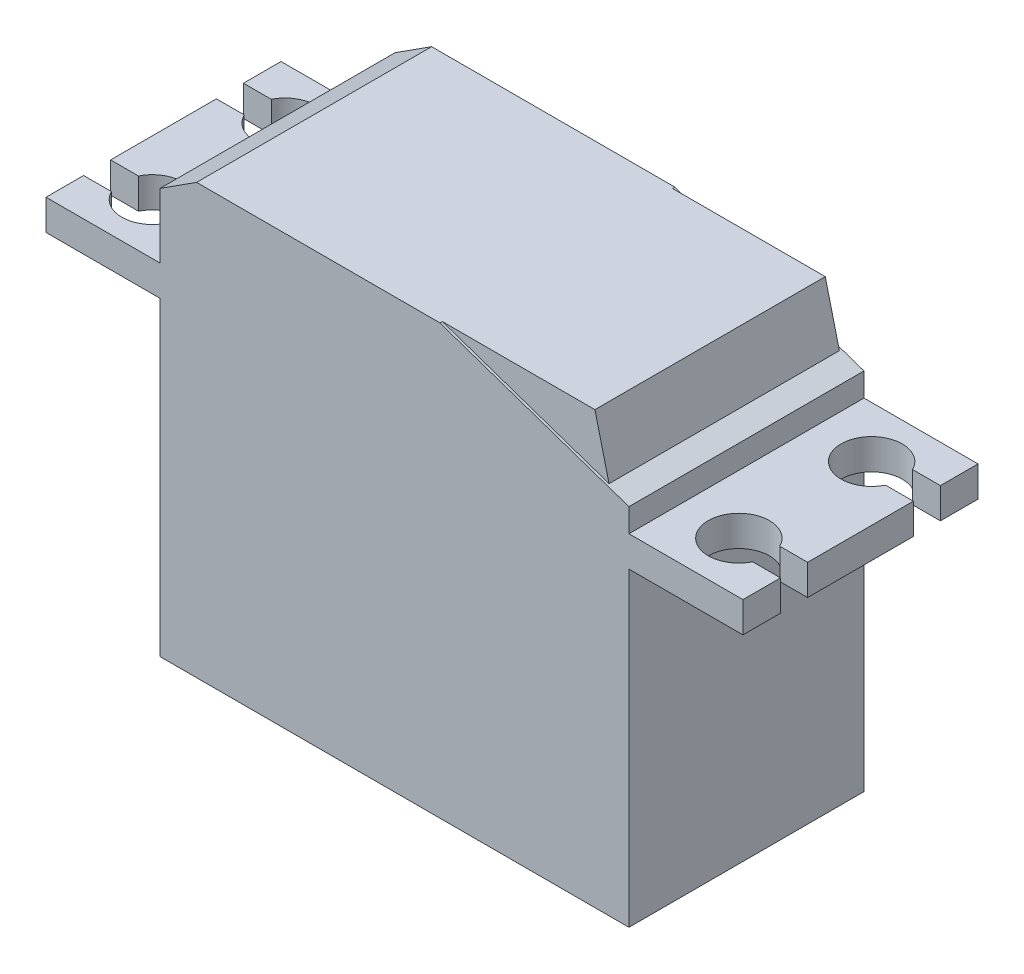
SolidWorks part; units mm, degrees
ref_plane "정면" through (0, 0, 0) normal (0, 0, 1) x (1, 0, 0)
ref_plane "윗면" through (0, 0, 0) normal (0, 1, 0) x (1, 0, 0)
ref_plane "우측면" through (0, 0, 0) normal (1, 0, 0) x (0, 0, -1)
sketch "Sketch1" plane through (0, 0, 0) normal (0, 1, 0) x (1, 0, 0)
  line L1 (-19.95, 10) -> (19.95, 10)
  line L2 (-19.95, 10) -> (-19.95, -10)
  line L3 (-19.95, -10) -> (19.95, -10)
  line L4 (19.95, 10) -> (19.95, -10)
  line L5 (-19.95, 10) -> (19.95, -10) construction
  line L6 (-19.95, -10) -> (19.95, 10) construction
  point P0 (0, 0)
  dimension "D1" = 20
  dimension "D2" = 39.9
extrude "Boss-Extrude1" add sketch "Sketch1" along normal mid plane 36.5
sketch "Sketch2" plane through (19.95, 0, 0) normal (1, 0, 0) x (0, 0, -1)
  line L0 (-10, 8.15) -> (10, 8.15)
  line L1 (-10, 18.25) -> (-10, -18.25) construction
  line L2 (10, 18.25) -> (10, -18.25) construction
  line L3 (-10, -18.25) -> (10, -18.25) construction
  line L4 (-10, 10.75) -> (10, 10.75)
  line L5 (-10, 10.75) -> (-10, 8.15)
  line L6 (10, 10.75) -> (10, 8.15)
  dimension "D1" = 26.4
  dimension "D2" = 2.6
extrude "Boss-Extrude2" add sketch "Sketch2" along normal blind 9.7
sketch "Sketch3" plane through (0, 0, 10) normal (0, 0, 1) x (1, 0, 0)
  line L0 (19.95, 12.75) -> (3.8643, 18.25)
  line L1 (19.95, 18.25) -> (19.95, 10.75) construction
  line L2 (-19.95, 18.25) -> (19.95, 18.25) construction
  line L3 (3.8643, 18.25) -> (19.95, 18.25)
  line L4 (19.95, 18.25) -> (19.95, 12.75)
  dimension "D1" = 17
  dimension "D2" = 2
extrude "Cut-Extrude1" cut sketch "Sketch3" against normal through all
sketch "Sketch5" plane through (0, 0, 10) normal (0, 0, 1) x (1, 0, 0)
  line L0 (3.8643, 18.25) -> (16.8538, 18.25)
  line L1 (16.8538, 18.25) -> (18.0576, 13.3971)
  line L2 (3.8643, 18.25) -> (19.95, 12.75) construction
  line L3 (3.8643, 18.25) -> (18.0576, 13.3971)
  dimension "D1" = 5
  dimension "D2" = 2
extrude "Boss-Extrude3" add sketch "Sketch5" against normal blind 19.8
sketch "Sketch7" plane through (0, 10.75, 0) normal (0, 1, 0) x (1, 0, 0)
  line L0 (19.95, 0) -> (29.65, 0) construction
  line L1 (24.95, 8.25) -> (24.95, 3.05) construction
  line L3 (19.95, 10) -> (19.95, -10) construction
  line L4 (29.65, 10) -> (29.65, -10) construction
  line L5 (26.47, 5.65) -> (22.35, 5.65) construction
  line L6 (29.65, 10) -> (19.95, 10) construction
  line L7 (29.65, 6.8) -> (27.2818, 6.8)
  line L8 (29.65, 4.5) -> (27.2818, 4.5)
  line L9 (29.65, -6.8) -> (27.2818, -6.8)
  line L10 (29.65, -4.5) -> (27.2818, -4.5)
  line L11 (29.65, 6.8) -> (29.65, 4.5)
  line L12 (29.65, -6.8) -> (29.65, -4.5)
  arc A0 (27.2818, 6.8) -> (27.2818, 4.5) centre (24.95, 5.65) ccw
  arc A1 (27.2818, -6.8) -> (27.2818, -4.5) centre (24.95, -5.65) cw
  point P8 (24.8, 0)
  point P13 (29.65, 6.8)
  dimension "D2" = 5.2
  dimension "D1" = 3.05
  dimension "D3" = 3.18
  dimension "D4" = 3.2
  dimension "D5" = 4.7
extrude "Cut-Extrude2" cut sketch "Sketch7" against normal up to next
sketch "Sketch9" plane through (0, 0, 10) normal (0, 0, 1) x (1, 0, 0)
  line L0 (16.8538, 18.25) -> (3.8643, 18.25) construction
  line L1 (18.0576, 13.3971) -> (16.8538, 18.25) construction
  line L2 (3.8643, 18.25) -> (18.0576, 13.3971) construction
  line L3 (16.8538, 18.25) -> (3.8643, 18.25)
  line L4 (18.0576, 13.3971) -> (16.8538, 18.25)
  line L5 (3.8643, 18.25) -> (18.0576, 13.3971)
extrude "Cut-Extrude4" cut sketch "Sketch9" against normal blind 0.2
sketch "Sketch10" plane through (0, 0, -10) normal (0, 0, -1) x (-1, 0, 0)
  line L0 (16.8371, 18.25) -> (19.95, 16.25)
  line L1 (-3.8643, 18.25) -> (19.95, 18.25) construction
  line L2 (19.95, 18.25) -> (19.95, -18.25) construction
  line L3 (19.95, 16.25) -> (19.95, 18.25)
  line L4 (19.95, 18.25) -> (16.8371, 18.25)
  dimension "D1" = 3.7
  dimension "D2" = 2
extrude "Cut-Extrude5" cut sketch "Sketch10" against normal up to next
mirror "Mirror1" about plane through (0, 0, 0) normal (1, 0, 0) of "Cut-Extrude2", "Boss-Extrude2"
